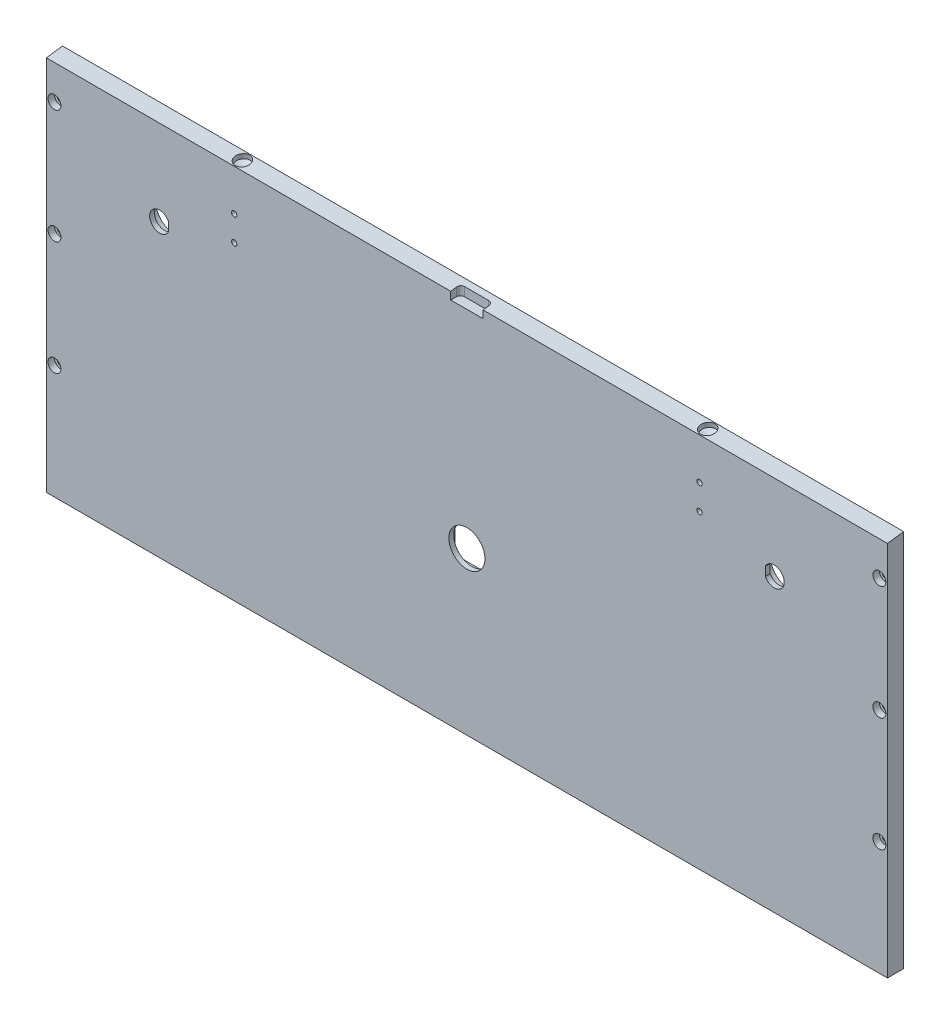
SolidWorks part; units mm, degrees
material "Bakelite Black"
ref_plane "Front" through (0, 0, 0) normal (0, 0, 1) x (1, 0, 0)
ref_plane "Top" through (0, 0, 0) normal (0, 1, 0) x (1, 0, 0)
ref_plane "Right" through (0, 0, 0) normal (1, 0, 0) x (0, 0, -1)
sketch "Sketch1" plane through (0, 0, 0) normal (0, 0, 1) x (1, 0, 0)
  line L1 (0, 0) -> (520, 0)
  line L2 (0, 0) -> (0, 234)
  line L3 (0, 234) -> (520, 234)
  line L4 (520, 0) -> (520, 234)
  dimension "D1" = 234
  dimension "D2" = 520
extrude "Boss-Extrude1" add sketch "Sketch1" along normal blind 10
ref_plane "Plane1" through (260, 0, 0) normal (-1, 0, 0) x (0, 0, 1)
sketch "Sketch8" plane through (0, 0, 10) normal (0, 0, 1) x (1, 0, 0)
  line L0 (260, 5.5) -> (260, -5.5) construction
  line L1 (250, 228) -> (270, 228)
  line L2 (250, 228) -> (250, 236)
  line L3 (250, 236) -> (270, 236)
  line L4 (270, 228) -> (270, 236)
  line L5 (250, 228) -> (270, 236) construction
  line L6 (250, 236) -> (270, 228) construction
  line L7 (520, 234) -> (0, 234) construction
  point P0 (260, 232)
  dimension "D1" = 20
  dimension "D2" = 8
  dimension "D3" = 6
extrude "Cut-Extrude5" cut sketch "Sketch8" against normal blind 6
fillet "Fillet2" radius 2.5 2 edges at (270, 231, 4) (250, 231, 4)
sketch "Sketch9" plane through (0, 0, 0) normal (1, 0, 0) x (0, 0, -1)
  line L0 (0, 234) -> (-10, 232.6853)
  line L1 (-10, 234) -> (-10, 0) construction
  line L2 (-10, 232.6853) -> (-10, 234)
  line L3 (-10, 234) -> (0, 234)
  dimension "D1" = 7.49
extrude "Cut-Extrude7" cut sketch "Sketch9" along normal through all
hole_wizard "M4x0.7 Tapped Hole1" positions "Sketch10" profile "Sketch11" tap size "M4x0.7" standard "ANSI Metric"
sketch "Sketch10" plane through (0, 0, 0) normal (0, -1, 0) x (-1, 0, 0)
  line L0 (-260, -8.8296) -> (-260, 8.8296) construction
  line L1 (0, 0) -> (-520, 0) construction
  point P0 (-70, -5)
  point P2 (-260, -5)
  point P4 (-450, -5)
  dimension "D1" = 190
  dimension "D2" = 190
  dimension "D3" = 5
sketch "Sketch11" plane through (70, 0, 5) normal (1, 0, 0) x (0, 0, -1)
  line L0 (0, 0) -> (0, 12.9914)
  line L1 (0, 12.9914) -> (1.65, 12)
  line L2 (1.65, 12) -> (1.65, 0)
  line L5 (1.65, 0) -> (0, 0)
  line L10 (0, 12.9914) -> (-1.65, 12) construction
  line L11 (0, -6.35) -> (0, 107.95) construction
  dimension "Tap Drill Dia." = 3.3
  dimension "Tap Drill Depth" = 12
  dimension "Drill Angle" = 118
cosmetic thread "Hole Thread1" parameters "D1"=8, "D2"=4
cosmetic thread "Hole Thread2" parameters "D1"=8, "D2"=4
cosmetic thread "Hole Thread3" parameters "D1"=8, "D2"=4
hole_wizard "CBORE for M4 SHCS1" positions "Sketch12" profile "Sketch13" counterbore size "M4" standard "ANSI Metric"
sketch "Sketch12" plane through (0, 0, 10) normal (0, 0, 1) x (1, 0, 0)
  line L0 (0, 0) -> (520, 0) construction
  line L1 (0, 232.6853) -> (0, 0) construction
  point P0 (5, 211.5)
  point P2 (5, 141)
  point P4 (5, 70.5)
  dimension "D1" = 70.5
  dimension "D2" = 70.5
  dimension "D3" = 70.5
  dimension "D4" = 5
sketch "Sketch13" plane through (5, 211.5, 10) normal (1, 0, 0) x (0, -1, 0)
  line L0 (0, 0) -> (0, 13.3519)
  line L1 (0, 13.3519) -> (2.25, 12)
  line L2 (2.25, 12) -> (2.25, 4)
  line L3 (2.25, 4) -> (4, 4)
  line L4 (4, 4) -> (4, 0)
  line L5 (4, 0) -> (0, 0)
  line L10 (0, 13.3519) -> (-2.25, 12) construction
  line L11 (0, -6.35) -> (0, 107.95) construction
  dimension "Hole Dia." = 4.5
  dimension "Hole Depth" = 12
  dimension "C'Bore Dia." = 8
  dimension "C'Bore Depth" = 4
  dimension "Drill Angle" = 118
mirror "Mirror1" about plane through (260, 0, 0) normal (-1, 0, 0) of "CBORE for M4 SHCS1"
hole_wizard "M4x0.7 Tapped Hole2" positions "Sketch14" profile "Sketch15" tap size "M4x0.7" standard "ANSI Metric" end condition through all
sketch "Sketch14" plane through (0, 0, 10) normal (0, 0, 1) x (1, 0, 0)
  line L0 (250, 232.6853) -> (0, 232.6853) construction
  line L1 (260, 8.8296) -> (260, -8.8296) construction
  point P0 (116.15, 207.1853)
  point P2 (116.15, 191.6853)
  dimension "D1" = 15.5
  dimension "D2" = 25.5
  dimension "D3" = 143.85
sketch "Sketch15" plane through (116.15, 207.1853, 10) normal (1, 0, 0) x (0, -1, 0)
  line L0 (0, 0) -> (0, 10)
  line L1 (0, 10) -> (1.65, 10)
  line L2 (1.65, 10) -> (1.65, 0)
  line L5 (1.65, 0) -> (0, 0)
  line L11 (0, -6.35) -> (0, 107.95) construction
  dimension "Thru Tap Drill Dia." = 3.3
  dimension "Thru Tap Drill Depth" = 10
cosmetic thread "Hole Thread4" parameters "D2"=4
cosmetic thread "Hole Thread5" parameters "D2"=4
mirror "Mirror2" about plane through (260, 0, 0) normal (-1, 0, 0) of "M4x0.7 Tapped Hole2"
hole_wizard "Ø9.0 (9) Diameter Hole1" positions "Sketch16" profile "Sketch17" hole size "Ø9.0" standard "ANSI Metric"
sketch "Sketch16" plane through (0, 230.0239, 30.2424) normal (0, 0.9915, 0.1304) x (1, 0, 0)
  line L0 (260, 8.8296) -> (260, -8.8296) construction
  line L1 (520, 30.5026) -> (0, 30.5026) construction
  point P0 (116.15, 25.5026)
  dimension "D1" = 143.85
  dimension "D2" = 5
sketch "Sketch17" plane through (116.15, 233.3482, 4.9573) normal (1, 0, 0) x (0, -0.1304, 0.9915)
  line L0 (0, 0) -> (0, 5.7039)
  line L1 (0, 5.7039) -> (4.5, 3)
  line L2 (4.5, 3) -> (4.5, 0)
  line L5 (4.5, 0) -> (0, 0)
  line L10 (0, 5.7039) -> (-4.5, 3) construction
  line L11 (0, -6.35) -> (0, 107.95) construction
  dimension "Hole Dia." = 9
  dimension "Hole Depth" = 3
  dimension "Drill Angle" = 118
mirror "Mirror5" about plane through (260, 0, 0) normal (-1, 0, 0) of "Ø9.0 (9) Diameter Hole1"
sketch "Sketch18" plane through (0, 0, 10) normal (0, 0, 1) x (1, 0, 0)
  line L0 (0, 0) -> (520, 0) construction
  line L1 (260, 8.8296) -> (260, -8.8296) construction
  circle A0 centre (260, 100) radius 11.15
  dimension "D1" = 22.3
  dimension "D2" = 100
extrude "Cut-Extrude8" cut sketch "Sketch18" against normal through all
sketch "Sketch19" plane through (0, 0, 0) normal (0, 0, -1) x (-1, 0, 0)
  line L0 (-260, -8.8296) -> (-260, 8.8296) construction
  line L5 (-277.5, 83) -> (-242.5, 83)
  line L6 (-277.5, 83) -> (-277.5, 130)
  line L7 (-277.5, 130) -> (-242.5, 130)
  line L8 (-242.5, 83) -> (-242.5, 130)
  circle A1 centre (-260, 100) radius 11.15 construction
  point P5 (-260, 83)
  dimension "D1" = 35
  dimension "D3" = 17
  dimension "D2" = 30
extrude "Cut-Extrude9" cut sketch "Sketch19" against normal blind 7
fillet "Fillet3" radius 2 4 edges at (242.5, 83, 3.5) (242.5, 130, 3.5) (277.5, 130, 3.5) (277.5, 83, 3.5)
sketch "Sketch20" plane through (0, 0, 0) normal (0, 0, -1) x (-1, 0, 0)
  line L0 (-75.5, 177.2482) -> (-75.5, 182.7518)
  line L1 (0, 234) -> (0, 0) construction
  line L2 (0, 0) -> (-520, 0) construction
  arc A0 (-75.5, 177.2482) -> (-75.5, 182.7518) centre (-70, 180) ccw
  dimension "D1" = 12.3
  dimension "D2" = 5.5
  dimension "D3" = 70
  dimension "D4" = 180
extrude "Cut-Extrude10" cut sketch "Sketch20" against normal through all
mirror "Mirror6" about plane through (260, 0, 0) normal (-1, 0, 0) of "Cut-Extrude10"
sketch "Sketch21" plane through (0, 0, 0) normal (0, 0, -1) x (-1, 0, 0)
  circle A0 centre (-70, 180) radius 12.5
  dimension "D1" = 25
extrude "Cut-Extrude11" cut sketch "Sketch21" against normal blind 7
mirror "Mirror7" about plane through (260, 0, 0) normal (-1, 0, 0) of "Cut-Extrude11"
